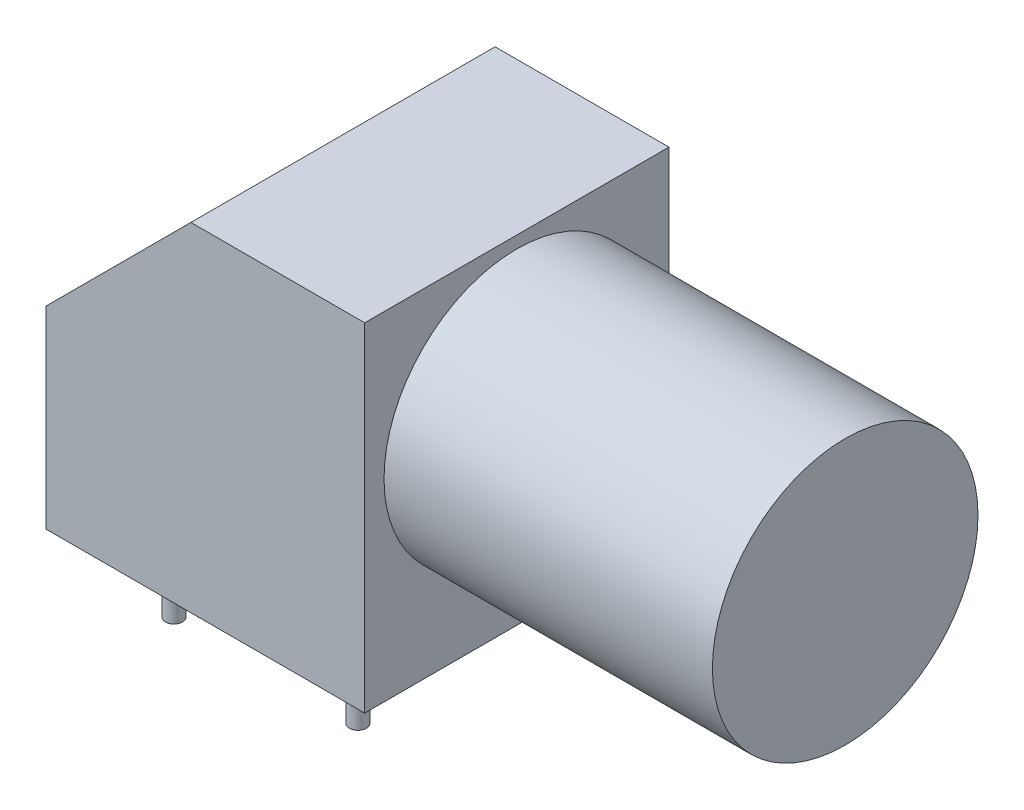
SolidWorks part; units mm, degrees
material "ABS"
ref_plane "Plan de face" through (0, 0, 0) normal (0, 0, 1) x (1, 0, 0)
ref_plane "Plan de dessus" through (0, 0, 0) normal (0, 1, 0) x (1, 0, 0)
ref_plane "Plan de droite" through (0, 0, 0) normal (1, 0, 0) x (0, 0, -1)
sketch "Esquisse1" plane through (0, 0, 0) normal (0, 1, 0) x (1, 0, 0)
  line L1 (0, 0) -> (13.2, 0)
  line L2 (0, 0) -> (0, 12.6)
  line L3 (0, 12.6) -> (13.2, 12.6)
  line L4 (13.2, 0) -> (13.2, 12.6)
  dimension "D1" = 13.2
  dimension "D2" = 12.6
extrude "Extrusion1" add sketch "Esquisse1" along normal blind 14
chamfer "Chanfrein1" distance 6 angle 45 1 edges at (0, 14, -6.3)
sketch "Esquisse2" plane through (13.2, 0, 0) normal (1, 0, 0) x (0, 0, -1)
  line L0 (6.3, 14) -> (6.3, 0) construction
  line L1 (0, 14) -> (12.6, 14) construction
  line L2 (0, 0) -> (12.6, 0) construction
  circle A0 centre (6.3, 8) radius 5.5
  dimension "D1" = 8
extrude "Extrusion2" add sketch "Esquisse2" along normal blind 13.6
sketch "Esquisse3" plane through (0, 0, 0) normal (0, -1, 0) x (1, 0, 0)
  line L0 (-1.3486, -6.3) -> (14.7577, -6.3) construction
  line L1 (2.81, 1.5113) -> (2.81, -14.9297) construction
  line L2 (10.43, 2.4785) -> (10.43, -15.6364) construction
  line L3 (0, -12.6) -> (0, 0) construction
  line L4 (14.4601, -10.11) -> (-1.3486, -10.11) construction
  line L5 (14.4601, -2.49) -> (-1.0882, -2.49) construction
  circle A0 centre (10.43, -2.49) radius 0.35
  circle A1 centre (10.43, -10.11) radius 0.35
  circle A2 centre (2.81, -2.49) radius 0.35
  circle A3 centre (2.81, -10.11) radius 0.35
  dimension "D1" = 2.81
  dimension "D2" = 7.62
  dimension "D3" = 3.81
  dimension "D4" = 3.81
extrude "Extrusion3" add sketch "Esquisse3" along normal blind 3
